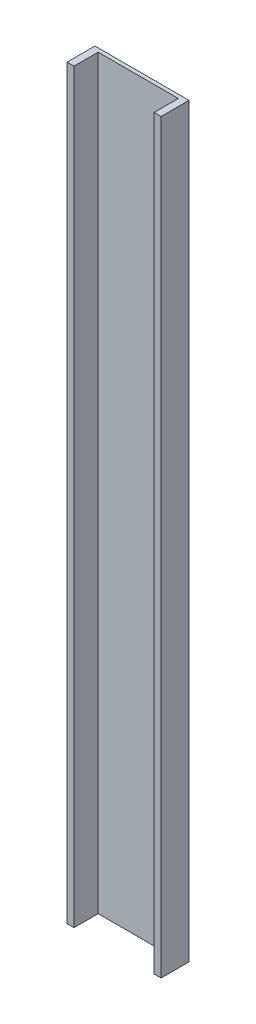
SolidWorks part; units mm, degrees
ref_plane "Plan de face" through (0, 0, 0) normal (0, 0, 1) x (1, 0, 0)
ref_plane "Plan de dessus" through (0, 0, 0) normal (0, 1, 0) x (1, 0, 0)
ref_plane "Plan de droite" through (0, 0, 0) normal (1, 0, 0) x (0, 0, -1)
sketch "Sketch1" plane through (0, 0, 0) normal (0, 1, 0) x (1, 0, 0)
  line L0 (-6.5, -4) -> (-6.5, 2.9388)
  line L1 (18.5, -4) -> (16.5, -4)
  line L2 (18.5, -4) -> (18.5, 4)
  line L3 (18.5, 4) -> (-8.5, 4)
  line L4 (-8.5, -4) -> (-8.5, 4)
  line L7 (-6.5, 2.9388) -> (16.5, 2.9388)
  line L8 (16.5, 2.9388) -> (16.5, -4)
  line L9 (-6.5, -4) -> (-8.5, -4)
  point P0 (0, 0)
  dimension "D1" = 27
  dimension "D2" = 8
  dimension "D3" = 23
  dimension "D4" = 2
extrude "Boss-Extrude1" add sketch "Sketch1" along normal blind 214
